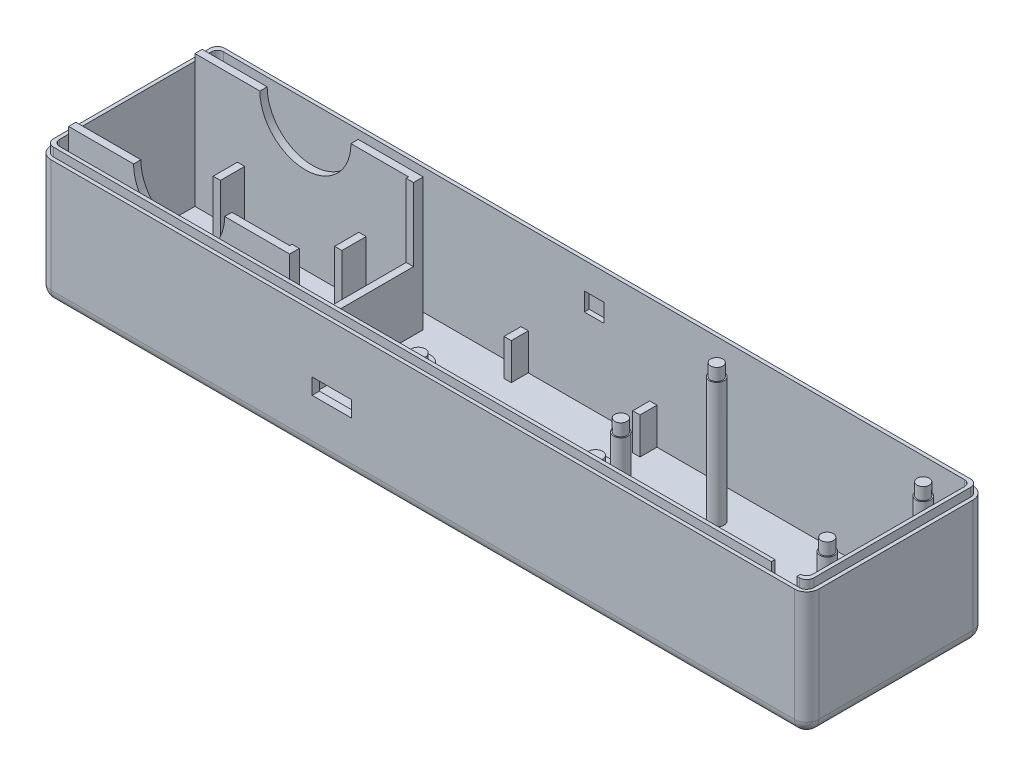
SolidWorks part; units mm, degrees
ref_plane "Front Plane" through (0, 0, 0) normal (0, 0, 1) x (1, 0, 0)
ref_plane "Top Plane" through (0, 0, 0) normal (0, 1, 0) x (1, 0, 0)
ref_plane "Right Plane" through (0, 0, 0) normal (1, 0, 0) x (0, 0, -1)
sketch "Sketch1" plane through (0, 0, 0) normal (0, 1, 0) x (1, 0, 0)
  line L1 (-80.2894, -18.669) -> (80.2894, -18.669)
  line L2 (-80.2894, -18.669) -> (-80.2894, 18.669)
  line L3 (-80.2894, 18.669) -> (80.2894, 18.669)
  line L4 (80.2894, -18.669) -> (80.2894, 18.669)
  line L5 (-80.2894, -18.669) -> (80.2894, 18.669) construction
  line L6 (-80.2894, 18.669) -> (80.2894, -18.669) construction
  point P0 (0, 0)
  dimension "D1" = 160.5788
  dimension "D2" = 37.338
extrude "Boss-Extrude1" add sketch "Sketch1" along normal blind 27.94
sketch "Sketch2" plane through (0, 27.94, 0) normal (0, 1, 0) x (1, 0, 0)
  line L0 (-80.2894, 18.669) -> (-80.2894, -18.669) construction
  line L1 (-78.7654, 17.145) -> (78.7654, 17.145)
  line L2 (-78.7654, 17.145) -> (-78.7654, -17.145)
  line L3 (-78.7654, -17.145) -> (78.7654, -17.145)
  line L4 (78.7654, 17.145) -> (78.7654, -17.145)
  line L5 (-78.7654, 17.145) -> (78.7654, -17.145) construction
  line L6 (-78.7654, -17.145) -> (78.7654, 17.145) construction
  line L7 (-80.2894, -18.669) -> (80.2894, -18.669) construction
  point P0 (0, 0)
  dimension "D1" = 1.524
  dimension "D2" = 1.524
extrude "Cut-Extrude3" cut sketch "Sketch2" against normal offset from surface (26.289 mm away) 1.651 up to face at (0, 0, 0)
fillet "Fillet1" radius 2.54 8 edges at (80.2894, 0, 0) (80.2894, 13.97, -18.669) (0, 0, -18.669) (0, 0, 18.669) (-80.2894, 0, 0) (-80.2894, 13.97, -18.669) (-80.2894, 13.97, 18.669) (80.2894, 13.97, 18.669)
fillet "Fillet2" radius 1.27 4 edges at (78.7654, 14.7955, 17.145) (78.7654, 14.7955, -17.145) (-78.7654, 14.7955, 17.145) (-78.7654, 14.7955, -17.145)
sketch "Sketch3" plane through (0, 1.651, 0) normal (0, 1, 0) x (1, 0, 0)
  line L0 (-78.7654, 15.875) -> (-78.7654, -15.875) construction
  line L1 (-78.7654, 13.97) -> (-32.5374, 13.97)
  line L2 (-78.7654, 13.97) -> (-78.7654, -13.97)
  line L3 (-78.7654, -13.97) -> (-32.5374, -13.97)
  line L4 (-32.5374, 13.97) -> (-32.5374, -13.97)
  line L5 (0, 0) -> (-41.9588, 0) construction
  dimension "D1" = 27.94
  dimension "D2" = 46.228
extrude "Boss-Extrude2" add sketch "Sketch3" along normal blind 27.686 contours L2 L1 L4 L3
sketch "Sketch8" plane through (0, 29.337, 0) normal (0, 1, 0) x (1, 0, 0)
  line L0 (-32.5374, 0) -> (-78.7654, 0) construction
  line L1 (-34.0614, 12.446) -> (-78.7654, 12.446)
  line L2 (-34.0614, 12.446) -> (-34.0614, -12.446)
  line L3 (-34.0614, -12.446) -> (-78.7654, -12.446)
  line L4 (-78.7654, 12.446) -> (-78.7654, -12.446)
  line L5 (-32.5374, 13.97) -> (-32.5374, -13.97) construction
  line L6 (-78.7654, 13.97) -> (-78.7654, -13.97) construction
  line L7 (-78.7654, 13.97) -> (-32.5374, 13.97) construction
  dimension "D1" = 1.524
  dimension "D2" = 1.524
extrude "Cut-Extrude6" cut sketch "Sketch8" against normal up to surface (27.686 mm away) up to face at (-18.5505, 1.651, 0)
sketch "Sketch7" plane through (0, 0, 13.97) normal (0, 0, 1) x (1, 0, 0)
  line L0 (-78.7654, 29.337) -> (-32.5374, 29.337) construction
  circle A0 centre (-55.6514, 29.337) radius 9.525
  dimension "D1" = 19.05
extrude "Cut-Extrude5" cut sketch "Sketch7" against normal up to surface (27.94 mm away) up to face at (-60.2742, 17.9832, -13.97)
sketch "Sketch9" plane through (-34.0614, 0, 0) normal (-1, 0, 0) x (0, 0, 1)
  line L0 (12.446, 29.337) -> (-12.446, 29.337) construction
  line L1 (-11.938, 29.337) -> (11.938, 29.337)
  line L2 (-11.938, 29.337) -> (-11.938, 14.097)
  line L3 (-11.938, 14.097) -> (11.938, 14.097)
  line L4 (11.938, 29.337) -> (11.938, 14.097)
  line L5 (-12.446, 1.651) -> (-12.446, 29.337) construction
  line L6 (12.446, 1.651) -> (12.446, 29.337) construction
  dimension "D1" = 0.508
  dimension "D2" = 0.508
  dimension "D3" = 15.24
extrude "Cut-Extrude7" cut sketch "Sketch9" against normal up to next
sketch "Sketch10" plane through (0, 1.651, 0) normal (0, 1, 0) x (1, 0, 0)
  line L0 (0, 0) -> (57.9787, 0) construction
  line L1 (-34.0614, 11.938) -> (-34.0614, -11.938) construction
  line L2 (-23.9014, 16.51) -> (21.8186, 16.51) construction
  line L3 (-23.9014, 16.51) -> (-23.9014, -16.51) construction
  line L4 (-23.9014, -16.51) -> (21.8186, -16.51) construction
  line L5 (21.8186, 16.51) -> (21.8186, -16.51) construction
  line L6 (77.4954, 17.145) -> (-77.4954, 17.145) construction
  line L7 (-15.2654, 17.145) -> (-13.7414, 17.145)
  line L8 (-15.2654, 17.145) -> (-15.2654, 13.589)
  line L9 (-15.2654, 13.589) -> (-13.7414, 13.589)
  line L10 (-13.7414, 17.145) -> (-13.7414, 13.589)
  line L11 (11.6586, 17.145) -> (13.1826, 17.145)
  line L12 (11.6586, 17.145) -> (11.6586, 13.589)
  line L13 (11.6586, 13.589) -> (13.1826, 13.589)
  line L14 (13.1826, 17.145) -> (13.1826, 13.589)
  line L15 (-15.2654, -13.589) -> (-13.7414, -13.589)
  line L16 (-15.2654, -13.589) -> (-15.2654, -17.145)
  line L17 (-15.2654, -17.145) -> (-13.7414, -17.145)
  line L18 (-13.7414, -13.589) -> (-13.7414, -17.145)
  line L19 (11.6586, -13.589) -> (13.1826, -13.589)
  line L20 (11.6586, -13.589) -> (11.6586, -17.145)
  line L21 (11.6586, -17.145) -> (13.1826, -17.145)
  line L22 (13.1826, -13.589) -> (13.1826, -17.145)
  line L23 (-77.4954, -17.145) -> (77.4954, -17.145) construction
  line L24 (-19.5834, 0) -> (17.5006, 0) construction
  line L25 (-1.0414, 0) -> (-1.0414, 27.8504) construction
  circle A0 centre (-19.5834, 0) radius 2.54
  circle A1 centre (17.5006, 0) radius 2.54
  dimension "D1" = 37.084
  dimension "D2" = 5.08
  dimension "D3" = 33.02
  dimension "D5" = 4.318
  dimension "D6" = 4.318
  dimension "D4" = 45.72
  dimension "D7" = 10.16
  dimension "D8" = 3.556
  dimension "D9" = 1.524
  dimension "D10" = 25.4
  dimension "D11" = 25.4
extrude "Boss-Extrude5" add sketch "Sketch10" along normal blind 7.62
sketch "Sketch11" plane through (0, 9.271, 0) normal (0, 1, 0) x (1, 0, 0)
  circle A0 centre (17.5006, 0) radius 1.4605
  circle A1 centre (-19.5834, 0) radius 1.4605
  dimension "D1" = 2.921
extrude "Boss-Extrude6" add sketch "Sketch11" along normal blind 1.651
sketch "Sketch12" plane through (0, 0, 18.669) normal (0, 0, 1) x (1, 0, 0)
  line L0 (77.7494, 0) -> (-77.7494, 0) construction
  line L1 (-23.1394, 14.1283) -> (-14.921, 14.1283)
  line L2 (-23.1394, 14.1283) -> (-23.1394, 10.795)
  line L3 (-23.1394, 10.795) -> (-14.921, 10.795)
  line L4 (-14.921, 14.1283) -> (-14.921, 10.795)
  line L5 (-80.2894, 27.94) -> (-80.2894, 2.54) construction
  dimension "D1" = 10.795
  dimension "D2" = 3.3333
  dimension "D3" = 8.2184
  dimension "D4" = 57.15
extrude "Cut-Extrude8" cut sketch "Sketch12" against normal up to next
sketch "Sketch13" plane through (0, 1.651, 0) normal (0, 1, 0) x (1, 0, 0)
  line L0 (78.7654, 0) -> (0, 0) construction
  line L1 (32.7914, 10.033) -> (75.9714, 10.033) construction
  line L2 (32.7914, 10.033) -> (32.7914, -10.033) construction
  line L3 (32.7914, -10.033) -> (75.9714, -10.033) construction
  line L4 (75.9714, 10.033) -> (75.9714, -10.033) construction
  line L5 (78.7654, -15.875) -> (78.7654, 15.875) construction
  circle A0 centre (32.7914, 10.033) radius 1.524
  circle A1 centre (75.9714, 10.033) radius 1.524
  circle A2 centre (75.9714, -10.033) radius 1.524
  circle A3 centre (32.7914, -10.033) radius 1.524
  dimension "D1" = 3.048
  dimension "D2" = 2.794
  dimension "D3" = 43.18
  dimension "D4" = 20.066
extrude "Boss-Extrude7" add sketch "Sketch13" along normal blind 26.162
sketch "Sketch14" plane through (0, 27.813, 0) normal (0, 1, 0) x (1, 0, 0)
  circle A0 centre (32.7914, 10.033) radius 1.27
  circle A1 centre (32.7914, -10.033) radius 1.27
  circle A2 centre (75.9714, -10.033) radius 1.27
  circle A3 centre (75.9714, 10.033) radius 1.27
  dimension "D1" = 2.54
extrude "Boss-Extrude8" add sketch "Sketch14" along normal blind 2.54
sketch "Sketch15" plane through (0, 1.651, 0) normal (0, 1, 0) x (1, 0, 0)
  line L0 (-78.7654, -12.446) -> (-34.0614, -12.446) construction
  line L1 (-42.9514, 12.446) -> (-44.4754, 12.446)
  line L2 (-42.9514, 12.446) -> (-42.9514, 7.366)
  line L3 (-42.9514, 7.366) -> (-44.4754, 7.366)
  line L4 (-44.4754, 12.446) -> (-44.4754, 7.366)
  line L5 (-42.9514, -7.366) -> (-44.4754, -7.366)
  line L6 (-42.9514, -7.366) -> (-42.9514, -12.446)
  line L7 (-42.9514, -12.446) -> (-44.4754, -12.446)
  line L8 (-44.4754, -7.366) -> (-44.4754, -12.446)
  line L9 (-68.3514, 12.446) -> (-69.8754, 12.446)
  line L10 (-68.3514, 12.446) -> (-68.3514, 7.366)
  line L11 (-68.3514, 7.366) -> (-69.8754, 7.366)
  line L12 (-69.8754, 12.446) -> (-69.8754, 7.366)
  line L13 (-69.8754, -12.446) -> (-68.3514, -12.446)
  line L14 (-69.8754, -12.446) -> (-69.8754, -7.366)
  line L15 (-69.8754, -7.366) -> (-68.3514, -7.366)
  line L16 (-68.3514, -12.446) -> (-68.3514, -7.366)
  line L17 (-34.0614, 12.446) -> (-78.7654, 12.446) construction
  line L18 (-34.0614, -12.446) -> (-34.0614, 12.446) construction
  line L19 (-78.7654, 12.446) -> (-78.7654, -12.446) construction
  point P22 (-42.9514, 9.906)
  dimension "D1" = 1.524
  dimension "D2" = 8.89
  dimension "D3" = 8.89
  dimension "D4" = 5.08
extrude "Boss-Extrude9" add sketch "Sketch15" along normal blind 12.446
sketch "Sketch16" plane through (0, 27.94, 0) normal (0, 1, 0) x (1, 0, 0)
  line L0 (77.7494, 18.669) -> (-77.7494, 18.669) construction
  line L1 (-79.5274, 17.907) -> (79.5274, 17.907)
  line L2 (-79.5274, 17.907) -> (-79.5274, -17.907)
  line L3 (-79.5274, -17.907) -> (79.5274, -17.907)
  line L4 (79.5274, 17.907) -> (79.5274, -17.907)
  line L5 (-80.2894, 16.129) -> (-80.2894, -16.129) construction
  line L6 (-77.7494, -18.669) -> (77.7494, -18.669) construction
  line L7 (80.2894, -16.129) -> (80.2894, 16.129) construction
  dimension "D1" = 0.762
  dimension "D2" = 0.762
  dimension "D3" = 0.762
  dimension "D4" = 0.762
extrude "Cut-Extrude9" cut sketch "Sketch16" against normal blind 1.778 flip side to cut
fillet "Fillet3" radius 1.524 4 edges at (-79.5274, 27.051, 17.907) (79.5274, 27.051, 17.907) (79.5274, 27.051, -17.907) (-79.5274, 27.051, -17.907)
sketch "Sketch17" plane through (0, 27.94, 0) normal (0, 1, 0) x (1, 0, 0)
  line L0 (-78.0034, -17.907) -> (78.0034, -17.907) construction
  line L1 (77.4954, -17.145) -> (72.1614, -17.145)
  line L2 (77.4954, -17.145) -> (77.4954, -17.907)
  line L3 (77.4954, -17.907) -> (72.1614, -17.907)
  line L4 (72.1614, -17.145) -> (72.1614, -17.907)
  dimension "D1" = 5.334
extrude "Cut-Extrude10" cut sketch "Sketch17" against normal blind 8.89
sketch "Sketch18" plane through (0, 0, 17.145) normal (0, 0, -1) x (-1, 0, 0)
  line L0 (-78.7654, 1.651) -> (-78.7654, 27.94) construction
  line L1 (-2.0574, 22.352) -> (2.0066, 22.352)
  line L2 (-2.0574, 22.352) -> (-2.0574, 18.542)
  line L3 (-2.0574, 18.542) -> (2.0066, 18.542)
  line L4 (2.0066, 22.352) -> (2.0066, 18.542)
  line L5 (77.4954, 27.94) -> (-72.1614, 27.94) construction
  dimension "D1" = 4.064
  dimension "D2" = 76.708
  dimension "D3" = 5.588
  dimension "D4" = 3.81
extrude "Cut-Extrude11" cut sketch "Sketch18" against normal blind 1.016
mirror "Mirror1" about plane through (0, 0, 0) normal (0, 0, 1) of "Cut-Extrude11"
